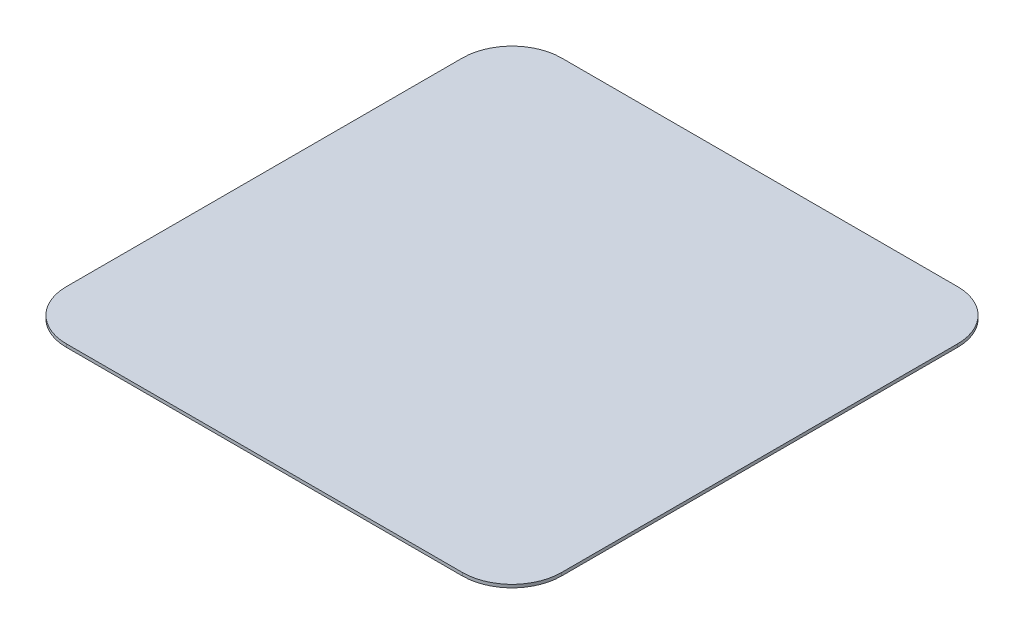
SolidWorks part; units mm, degrees
ref_plane "Front Plane" through (0, 0, 0) normal (0, 0, 1) x (1, 0, 0)
ref_plane "Top Plane" through (0, 0, 0) normal (0, 1, 0) x (1, 0, 0)
ref_plane "Right Plane" through (0, 0, 0) normal (1, 0, 0) x (0, 0, -1)
ref_plane "SheetPlane" through (0, 25.3275, 0) normal (0, 1, 0) x (1, 0, 0)
sketch "Sketch1" plane through (0, 25.3275, 0) normal (0, 1, 0) x (1, 0, 0)
  line L1 (-54.0192, -49.2656) -> (47.5808, -49.2656) construction
  line L2 (-66.7192, 65.0344) -> (-66.7192, -36.5656) construction
  line L3 (47.5808, 77.7344) -> (-54.0192, 77.7344) construction
  line L16 (60.2808, -36.5656) -> (60.2808, 65.0344)
  line L17 (-54.0192, -49.2656) -> (47.5808, -49.2656)
  line L18 (-66.7192, 65.0344) -> (-66.7192, -36.5656)
  line L19 (47.5808, 77.7344) -> (-54.0192, 77.7344)
  line L20 (60.2808, -36.5656) -> (60.2808, 65.0344) construction
  arc A0 (-54.0192, 77.7344) -> (-66.7192, 65.0344) centre (-54.0192, 65.0344) ccw construction
  arc A1 (-66.7192, -36.5656) -> (-54.0192, -49.2656) centre (-54.0192, -36.5656) ccw construction
  arc A2 (-54.0192, 77.7344) -> (-66.7192, 65.0344) centre (-54.0192, 65.0344) ccw
  arc A3 (47.5808, -49.2656) -> (60.2808, -36.5656) centre (47.5808, -36.5656) ccw construction
  arc A12 (47.5808, -49.2656) -> (60.2808, -36.5656) centre (47.5808, -36.5656) ccw
  arc A13 (60.2808, 65.0344) -> (47.5808, 77.7344) centre (47.5808, 65.0344) ccw construction
  arc A14 (60.2808, 65.0344) -> (47.5808, 77.7344) centre (47.5808, 65.0344) ccw
  arc A18 (-66.7192, -36.5656) -> (-54.0192, -49.2656) centre (-54.0192, -36.5656) ccw
extrude "MainBody" add sketch "Sketch1" along normal blind 0.7937
equation "\"SheetThickness\"= 0.03125in"
equation "\"D1@MainBody\" = \"SheetThickness\""
equation "\"SheetTolerance\"= 0.012in"
